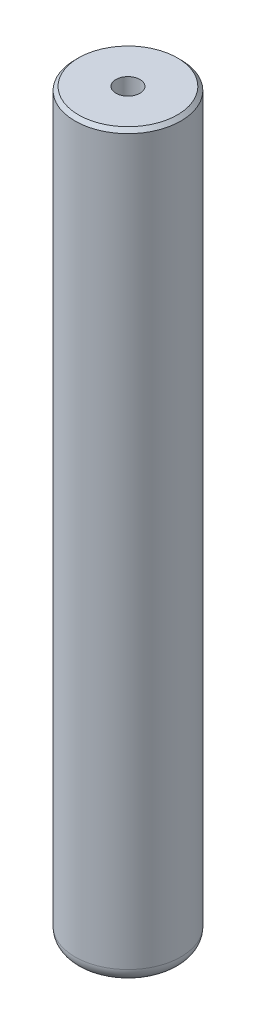
SolidWorks part; units mm, degrees
material "6061-T6 Aluminum"
ref_plane "Front Plane" through (0, 0, 0) normal (0, 0, 1) x (1, 0, 0)
ref_plane "Top Plane" through (0, 0, 0) normal (0, 1, 0) x (1, 0, 0)
ref_plane "Right Plane" through (0, 0, 0) normal (1, 0, 0) x (0, 0, -1)
sketch "Sketch1" plane through (0, 0, 0) normal (0, 1, 0) x (1, 0, 0)
  circle A0 centre (0, 0) radius 15
  dimension "D1" = 30
extrude "Boss-Extrude1" add sketch "Sketch1" along normal blind 210
fillet "Fillet1" radius 4 1 edges at (0, 0, 15)
chamfer "Chamfer1" distance 1 angle 45 1 edges at (0, 210, 15)
sketch "Sketch2" plane through (0, 210, 0) normal (0, 1, 0) x (1, 0, 0)
  point P0 (0, 0)
hole_wizard "M8x1.25 Tapped Hole1" positions "Sketch2" profile "Sketch3" tap size "M8x1.25" standard "ANSI Metric"
sketch "Sketch3" plane through (0, 210, 0) normal (1, 0, 0) x (0, 0, 1)
  line L0 (0, 0) -> (0, 21.7929)
  line L1 (0, 21.7929) -> (3.4, 19.75)
  line L2 (3.4, 19.75) -> (3.4, 0)
  line L5 (3.4, 0) -> (0, 0)
  line L10 (0, 21.7929) -> (-3.4, 19.75) construction
  line L11 (0, -6.35) -> (0, 107.95) construction
  dimension "Tap Drill Dia." = 6.8
  dimension "Tap Drill Depth" = 19.75
  dimension "Drill Angle" = 118
cosmetic thread "Hole Thread1" parameters "D1"=16, "D2"=8
